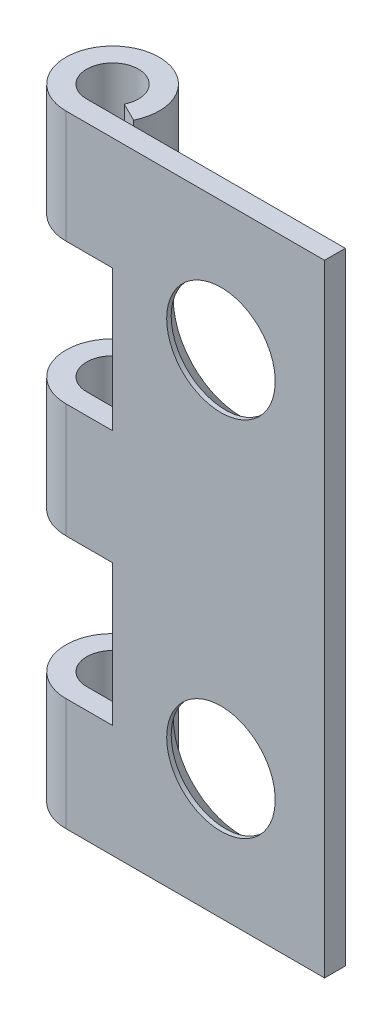
SolidWorks part; units mm, degrees
ref_plane "Front" through (0, 0, 0) normal (0, 0, 1) x (1, 0, 0)
ref_plane "Top" through (0, 0, 0) normal (0, 1, 0) x (1, 0, 0)
ref_plane "Right" through (0, 0, 0) normal (1, 0, 0) x (0, 0, -1)
sketch "Sketch1" plane through (0, 0, 0) normal (0, 1, 0) x (1, 0, 0)
  line L0 (0, -0.7937) -> (7.9248, -0.7937)
  line L1 (7.9248, -0.7937) -> (7.9248, -1.4287)
  line L2 (7.9248, -1.4287) -> (0, -1.4288)
  line L3 (1.2799, -0.635) -> (0.711, -0.3528)
  line L4 (0.711, -0.3528) -> (0, 0) construction
  line L5 (1.2799, -0.635) -> (1.2011, -0.7937) construction
  arc A0 (0.711, -0.3528) -> (0, -0.7937) centre (0, 0) ccw
  arc A1 (1.2799, -0.635) -> (0, -1.4288) centre (0, 0) ccw
  dimension "D1" = 0.1588
  dimension "K Pin Dia" = 1.5875
  dimension "B Half Width" = 7.9248
  dimension "M Mat'l Thickness" = 0.635
extrude "Extrude1" add sketch "Sketch1" along normal mid plane 19.05
ref_plane "Plane2" through (4.7498, 0, 0) normal (1, 0, 0) x (0, 0, -1)
sketch "Sketch7" plane through (4.7498, 0, 0) normal (1, 0, 0) x (0, 0, -1)
  line L0 (1.8223, 5.5562) -> (-3.6624, 5.5562) construction
  line L1 (-0.7937, 5.5562) -> (-0.7937, 7.6518)
  line L2 (-0.7937, 7.6518) -> (-1.2905, 7.2199)
  line L3 (-1.2905, 7.2199) -> (-1.4287, 7.2199)
  line L4 (-1.4287, 7.2199) -> (-1.4287, 5.5563)
  line L5 (-1.4287, 5.5563) -> (-0.7937, 5.5562)
  line L6 (-0.7937, 3.4607) -> (-1.2905, 3.8926) construction
  line L7 (-0.7937, 9.525) -> (-0.7937, -9.525) construction
  line L9 (-1.4287, 9.525) -> (-0.7937, 9.525) construction
  line L10 (-1.4287, 9.525) -> (-1.4287, -9.525) construction
  dimension "D1" = 82
  dimension "Screw Head Dia" = 4.191
  dimension "X Thru Dia" = 3.3274
  dimension "G" = 3.9688
revolve "Cut-Revolve1" cut sketch "Sketch7" angle 360 about L0
pattern_linear "LPattern2" count 2 spacing 11.1125 along (0, -1, 0) of "Cut-Revolve1"
sketch "Sketch4" plane through (0, 0, 0) normal (0, 0, 1) x (1, 0, 0)
  line L0 (-1.4288, 9.525) -> (-1.4288, 6.0706) construction
  line L1 (-1.4288, 6.0706) -> (1.4288, 6.0706)
  line L2 (1.4288, 6.0706) -> (1.4288, 1.7526)
  line L3 (1.4288, 1.7526) -> (-1.4288, 1.7526)
  line L4 (-1.4288, 1.7526) -> (-1.4288, -1.7526) construction
  line L5 (-1.4288, -1.7526) -> (1.4288, -1.7526)
  line L6 (1.4288, -1.7526) -> (1.4288, -6.0706)
  line L7 (1.4288, -6.0706) -> (-1.4288, -6.0706)
  line L8 (-1.4288, -6.0706) -> (-1.4288, -9.525) construction
  line L9 (7.9248, -9.525) -> (0, -9.525) construction
  line L10 (7.9248, 9.525) -> (0, 9.525) construction
  line L11 (-1.4288, 9.525) -> (-1.4288, -9.525) construction
  line L12 (1.4288, -9.525) -> (1.4288, 9.525) construction
  line L13 (-1.4288, -6.0706) -> (-1.4288, -1.7526)
  line L14 (-1.4288, 1.7526) -> (-1.4288, 6.0706)
  dimension "D" = 3.5052
  dimension "C" = 12.1412
extrude "Cut-Extrude1" cut sketch "Sketch4" against normal through all and the other way through all
sketch "Sketch5" plane through (0, 0, 0) normal (0, 0, 1) x (1, 0, 0)
  line L0 (1.4288, -1.7526) -> (1.4288, -6.0706) construction
  line L1 (-1.4288, -9.525) -> (1.4288, -9.525)
  line L2 (-1.4288, -9.525) -> (-1.4288, -6.0198)
  line L3 (-1.4288, -6.0198) -> (1.4288, -6.0198)
  line L4 (1.4288, -9.525) -> (1.4288, -6.0198)
  line L5 (-1.4288, -6.0706) -> (-1.4288, -1.7526) construction
  line L6 (-1.4288, -1.8034) -> (1.4288, -1.8034)
  line L7 (-1.4288, -1.8034) -> (-1.4288, 1.8034)
  line L8 (-1.4288, 1.8034) -> (1.4288, 1.8034)
  line L9 (1.4288, -1.8034) -> (1.4288, 1.8034)
  line L10 (1.4288, 6.0706) -> (1.4288, 1.7526) construction
  line L11 (-1.4288, 6.0706) -> (1.4288, 6.0706) construction
  line L12 (-1.4288, 9.525) -> (1.4288, 9.525)
  line L13 (-1.4288, 9.525) -> (-1.4288, 6.0198)
  line L14 (-1.4288, 6.0198) -> (1.4288, 6.0198)
  line L15 (1.4288, 9.525) -> (1.4288, 6.0198)
  line L16 (1.4288, 1.7526) -> (-1.4288, 1.7526) construction
  line L17 (-1.4288, -1.7526) -> (1.4288, -1.7526) construction
  line L18 (1.4288, -6.0706) -> (-1.4288, -6.0706) construction
  dimension "D1" = 0.0508
  dimension "D2" = 0.0508
  dimension "D3" = 0.0508
  dimension "D4" = 0.0508
sketch "Sketch6" plane through (0, 0, 0) normal (0, 1, 0) x (1, 0, 0)
  line L0 (0, 0) -> (0, 0.7912) construction
  line L1 (0, 0.7912) -> (0, 0.7937) construction
  circle A0 centre (0, 0) radius 0.7912
  arc A1 (0.711, -0.3528) -> (0, -0.7937) centre (0, 0) ccw construction
  dimension "D1" = 0.0025
equation "\"D1@Sketch1\"=\"M Mat'l Thickness@Sketch1\"/4"
